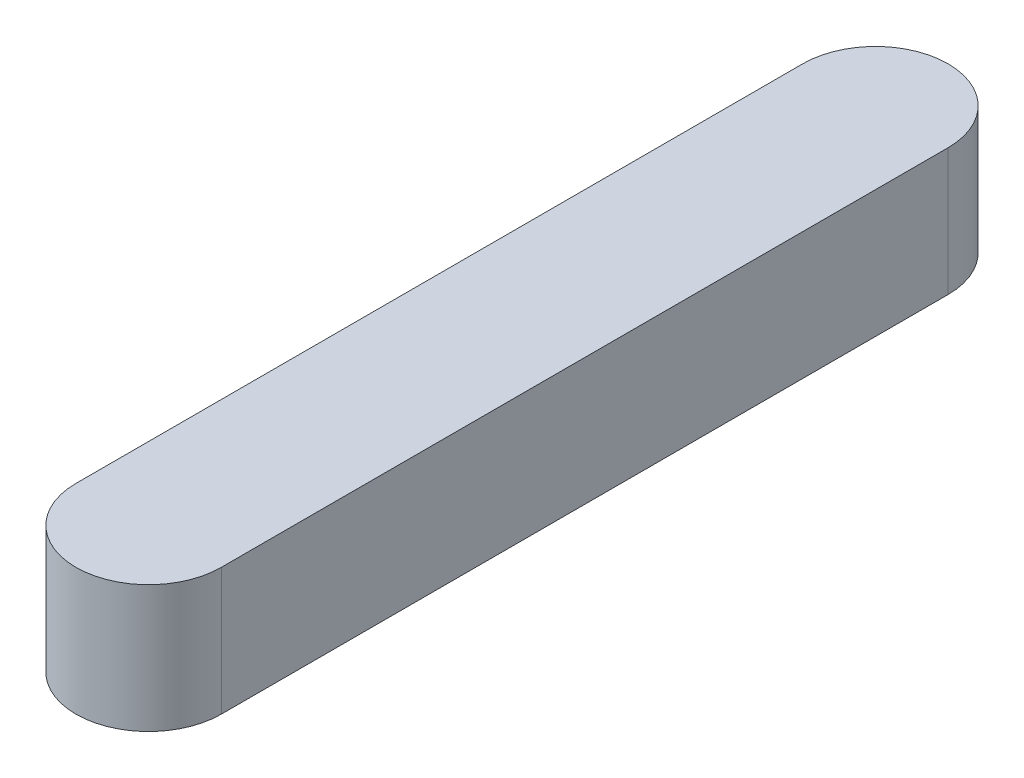
SolidWorks part; units mm, degrees
ref_plane "Front Plane" through (0, 0, 0) normal (0, 0, 1) x (1, 0, 0)
ref_plane "Top Plane" through (0, 0, 0) normal (0, 1, 0) x (1, 0, 0)
ref_plane "Right Plane" through (0, 0, 0) normal (1, 0, 0) x (0, 0, -1)
sketch "Sketch1" plane through (0, 0, 0) normal (0, 1, 0) x (1, 0, 0)
  line L0 (0, 20) -> (0, -20) construction
  line L1 (4, 20) -> (4, -20)
  line L2 (-4, 20) -> (-4, -20)
  arc A0 (4, 20) -> (-4, 20) centre (0, 20) ccw
  arc A1 (-4, -20) -> (4, -20) centre (0, -20) ccw
  point P2 (0, 0)
  dimension "D1" = 4
  dimension "D2" = 40
extrude "Boss-Extrude1" add sketch "Sketch1" along normal mid plane 7
